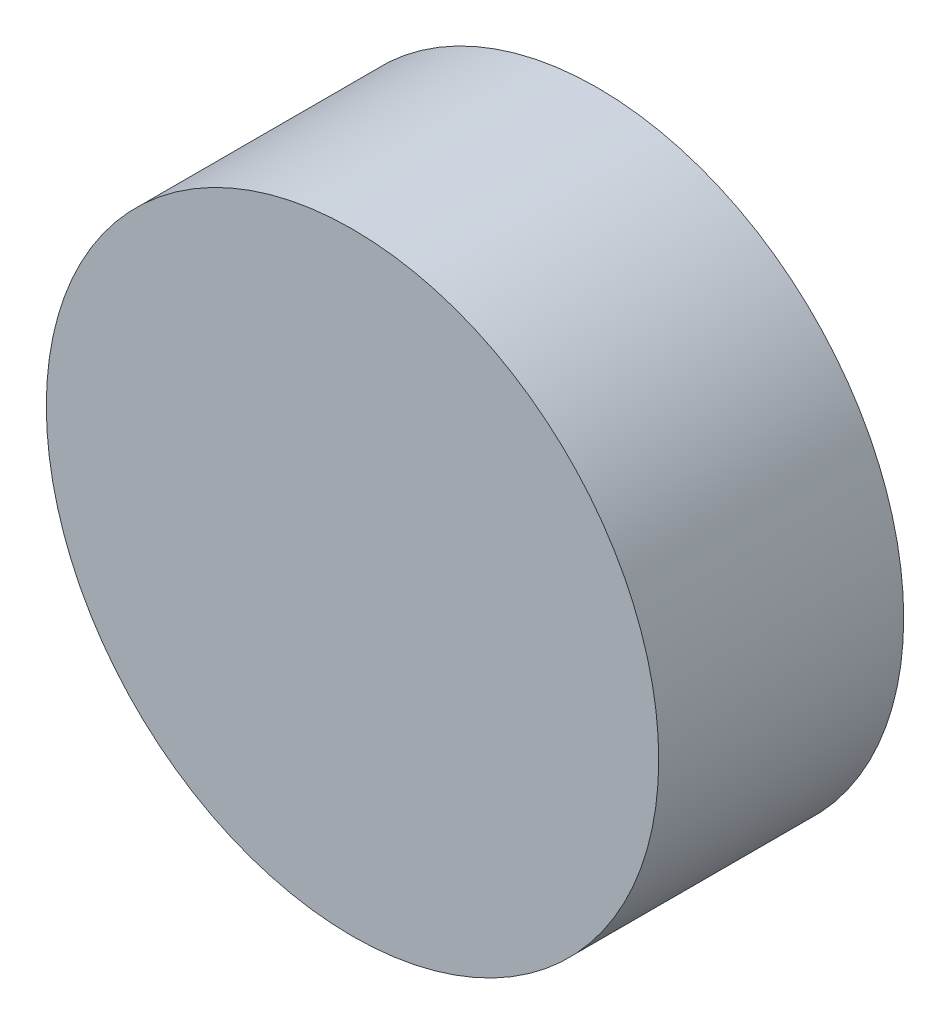
SolidWorks part; units mm, degrees
ref_plane "Front Plane" through (0, 0, 0) normal (0, 0, 1) x (1, 0, 0)
ref_plane "Top Plane" through (0, 0, 0) normal (0, 1, 0) x (1, 0, 0)
ref_plane "Right Plane" through (0, 0, 0) normal (1, 0, 0) x (0, 0, -1)
other "Configuration Table"
sketch "Sketch1" plane through (0, 0, 0) normal (0, 0, 1) x (1, 0, 0)
  circle A0 centre (0, 68) radius 25
extrude "KAP_helezon_topuz_D50" add sketch "Sketch1" against normal blind 20 from offset 700 separate body
